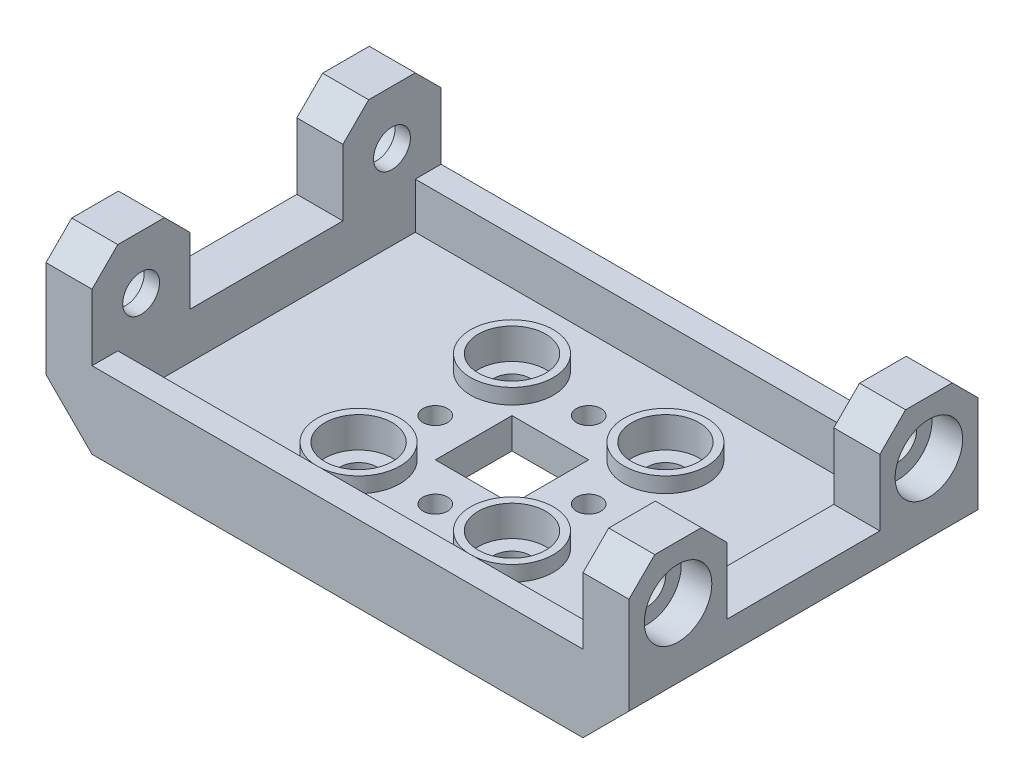
SolidWorks part; units mm, degrees
ref_plane "Front" through (0, 0, 0) normal (0, 0, 1) x (1, 0, 0)
ref_plane "Top" through (0, 0, 0) normal (0, 1, 0) x (1, 0, 0)
ref_plane "Right" through (0, 0, 0) normal (1, 0, 0) x (0, 0, -1)
sketch "草图1" plane through (0, 0, 0) normal (0, 1, 0) x (1, 0, 0)
  line L1 (-19, 11.375) -> (19, 11.375)
  line L2 (-19, 11.375) -> (-19, -11.375)
  line L3 (-19, -11.375) -> (19, -11.375)
  line L4 (19, 11.375) -> (19, -11.375)
  line L5 (-19, 11.375) -> (19, -11.375) construction
  line L6 (-19, -11.375) -> (19, 11.375) construction
  point P0 (0, 0)
  dimension "D1" = 38
  dimension "D2" = 22.75
extrude "凸台-拉伸1" add sketch "草图1" along normal blind 5
sketch "草图2" plane through (0, 5, 0) normal (0, 1, 0) x (1, 0, 0)
  line L0 (-19, -11.375) -> (19, -11.375) construction
  line L1 (-19, 11.375) -> (-16, 11.375)
  line L2 (-19, 11.375) -> (-19, -11.375)
  line L3 (-19, -11.375) -> (-16, -11.375)
  line L4 (-16, 11.375) -> (-16, -11.375)
  line L6 (19, 11.375) -> (16, 11.375)
  line L7 (19, 11.375) -> (19, -11.375)
  line L8 (19, -11.375) -> (16, -11.375)
  line L9 (16, 11.375) -> (16, -11.375)
  dimension "D1" = 3
  dimension "D2" = 3
sketch "草图6" plane through (0, 5, 0) normal (0, 1, 0) x (1, 0, 0)
  line L4 (16, -8.375) -> (16, 8.375)
  line L5 (16, -8.375) -> (16, 8.375)
  line L6 (-16, 8.375) -> (-16, -8.375)
  line L7 (-16, 8.375) -> (-16, -8.375)
  line L8 (-16, -8.375) -> (16, -8.375)
  line L14 (16, 8.375) -> (-16, 8.375)
  line L16 (-16, -8.375) -> (16, -8.375)
  line L18 (16, 8.375) -> (-16, 8.375)
  dimension "D1" = 3
extrude "切除-拉伸3" cut sketch "草图6" against normal blind 3
chamfer "倒角1" distance 3 angle 45 2 edges at (19, 0, 0) (-19, 0, 0)
sketch "草图7" plane through (0, 2, 0) normal (0, 1, 0) x (1, 0, 0)
  circle A0 centre (-5, 5) radius 2.7
  circle A1 centre (5, 5) radius 2.7
  circle A2 centre (5, -5) radius 2.7
  circle A3 centre (-5, -5) radius 2.7
  dimension "D1" = 5
  dimension "D2" = 5
  dimension "D3" = 2
  dimension "D4" = 2
extrude "凸台-拉伸5" add sketch "草图7" along normal blind 1
sketch "草图11" plane through (0, 2, 0) normal (0, 1, 0) x (1, 0, 0)
  point P3 (0, 5)
  point P5 (0, 0)
  point P6 (5, 0)
  point P7 (0, -5)
  point P9 (-5, 0)
extrude "凸台-拉伸4" add sketch "草图2" along normal blind 6
sketch "草图14" plane through (-19, 0, 0) normal (-1, 0, 0) x (0, 0, 1)
  line L0 (0, 11) -> (0, 0) construction
  line L1 (-11.375, 11) -> (11.375, 11) construction
  line L2 (-11.375, 11) -> (-11.375, 3) construction
  point P5 (-8.175, 7.5)
  point P8 (8.175, 7.5)
  dimension "D1" = 3.2
  dimension "D2" = 3.5
sketch "草图16" plane through (-19, 0, 0) normal (-1, 0, 0) x (0, 0, 1)
  line L0 (0, 11) -> (0, 0) construction
  line L1 (4.975, 5) -> (-4.975, 5)
  line L2 (4.975, 5) -> (4.975, 11)
  line L3 (4.975, 11) -> (-4.975, 11)
  line L4 (-4.975, 5) -> (-4.975, 11)
  line L5 (4.975, 5) -> (-4.975, 11) construction
  line L6 (4.975, 11) -> (-4.975, 5) construction
  line L7 (-11.375, 11) -> (11.375, 11) construction
  point P0 (0, 8)
  dimension "D1" = 9.95
extrude "切除-拉伸6" cut sketch "草图16" against normal through all
chamfer "倒角2" distance 1.68 angle 45 8 edges at (-17.5, 11, 11.375) (-17.5, 11, 4.975) (-17.5, 11, -4.975) (-17.5, 11, -11.375) (17.5, 11, -11.375) (17.5, 11, -4.975) (17.5, 11, 4.975) (17.5, 11, 11.375)
sketch "草图17" plane through (0, 5, 0) normal (0, 1, 0) x (1, 0, 0)
  line L0 (-16, -9.695) -> (16, -9.695)
  line L2 (16, -9.695) -> (16, -8.375)
  line L3 (16, -8.375) -> (-16, -8.375)
  line L4 (-16, -9.695) -> (-16, -8.375)
extrude "切除-拉伸7" cut sketch "草图17" against normal up to surface (3 mm away) up to face at (-5, 2, 7.7)
mirror "镜向2" about plane through (0, 0, 0) normal (0, 0, 1) of "切除-拉伸7"
sketch "草图18" plane through (0, 3, 0) normal (0, 1, 0) x (1, 0, 0)
  point P0 (-5, 5)
  point P3 (5, 5)
  point P5 (5, -5)
  point P6 (-5, -5)
  dimension "D1" = 2
hole_wizard "M2 凹头盖螺钉的柱形沉头孔2" positions "3D草图5" profile "草图19" counterbore size "M2" standard "ANSI Metric" end condition up to next
sketch3d "3D草图5"
  point P0 (-5, 3, -5)
  point P3 (5, 3, -5)
  point P6 (5, 3, 5)
  point P9 (-5, 3, 5)
sketch "草图19" plane through (-5, 3, -5) normal (1, 0, 0) x (0, 0, 1)
  line L0 (0, 0) -> (0, 3)
  line L1 (0, 3) -> (1.2, 3)
  line L3 (1.2, 3) -> (1.2, 2)
  line L4 (1.2, 2) -> (2.2, 2)
  line L5 (2.2, 2) -> (2.2, 0)
  line L7 (2.2, 0) -> (0, 0)
  line L11 (0, -6.35) -> (0, 107.95) construction
  dimension "通孔孔直径" = 2.4
  dimension "通孔孔深度" = 3
  dimension "柱形沉头孔直径" = 4.4
  dimension "柱形沉头孔深度" = 2
hole_wizard "M2x0.4 螺纹孔1" positions "3D草图6" profile "草图20" tap size "M2x0.4" standard "ANSI Metric" end condition up to next
sketch3d "3D草图6"
  point P0 (-5, 2, 0)
  point P3 (0, 2, -5)
  point P6 (5, 2, 0)
  point P9 (0, 2, 5)
sketch "草图20" plane through (-5, 2, 0) normal (1, 0, 0) x (0, 0, 1)
  line L0 (0, 0) -> (0, 2)
  line L1 (0, 2) -> (0.8, 2)
  line L2 (0.8, 2) -> (0.8, 0)
  line L5 (0.8, 0) -> (0, 0)
  line L11 (0, -6.35) -> (0, 107.95) construction
  dimension "通孔螺纹孔钻头直径" = 1.6
  dimension "通孔螺纹孔钻头深度" = 2
cosmetic thread "孔螺蚊线1" parameters "D2"=2
cosmetic thread "孔螺蚊线2" parameters "D2"=2
cosmetic thread "孔螺蚊线3" parameters "D2"=2
cosmetic thread "孔螺蚊线4" parameters "D2"=2
sketch "草图21" plane through (0, 2, 0) normal (0, 1, 0) x (1, 0, 0)
  line L1 (-2.5, 2.5) -> (2.5, 2.5)
  line L2 (-2.5, 2.5) -> (-2.5, -2.5)
  line L3 (-2.5, -2.5) -> (2.5, -2.5)
  line L4 (2.5, 2.5) -> (2.5, -2.5)
  line L5 (-2.5, 2.5) -> (2.5, -2.5) construction
  line L6 (-2.5, -2.5) -> (2.5, 2.5) construction
  point P0 (0, 0)
  dimension "D1" = 5
  dimension "D2" = 5
extrude "切除-拉伸8" cut sketch "草图21" against normal blind 10
hole_wizard "M2 凹头盖螺钉的柱形沉头孔3" positions "3D草图7" profile "草图22" counterbore size "M2" standard "ANSI Metric"
sketch3d "3D草图7"
  point P0 (-19, 7.5, -8.175)
  point P3 (-19, 7.5, 8.175)
sketch "草图22" plane through (-19, 7.5, -8.175) normal (0, 1, 0) x (0, 0, 1)
  line L0 (0, 0) -> (0, 38)
  line L1 (0, 38) -> (1.2, 38)
  line L3 (1.2, 38) -> (1.2, 2)
  line L4 (1.2, 2) -> (2.2, 2)
  line L5 (2.2, 2) -> (2.2, 0)
  line L7 (2.2, 0) -> (0, 0)
  line L11 (0, -6.35) -> (0, 107.95) construction
  dimension "通孔孔直径" = 2.4
  dimension "通孔孔深度" = 38
  dimension "柱形沉头孔直径" = 4.4
  dimension "柱形沉头孔深度" = 2
mirror "镜向3" about plane through (0, 0, 0) normal (1, 0, 0) of "M2 凹头盖螺钉的柱形沉头孔3"
